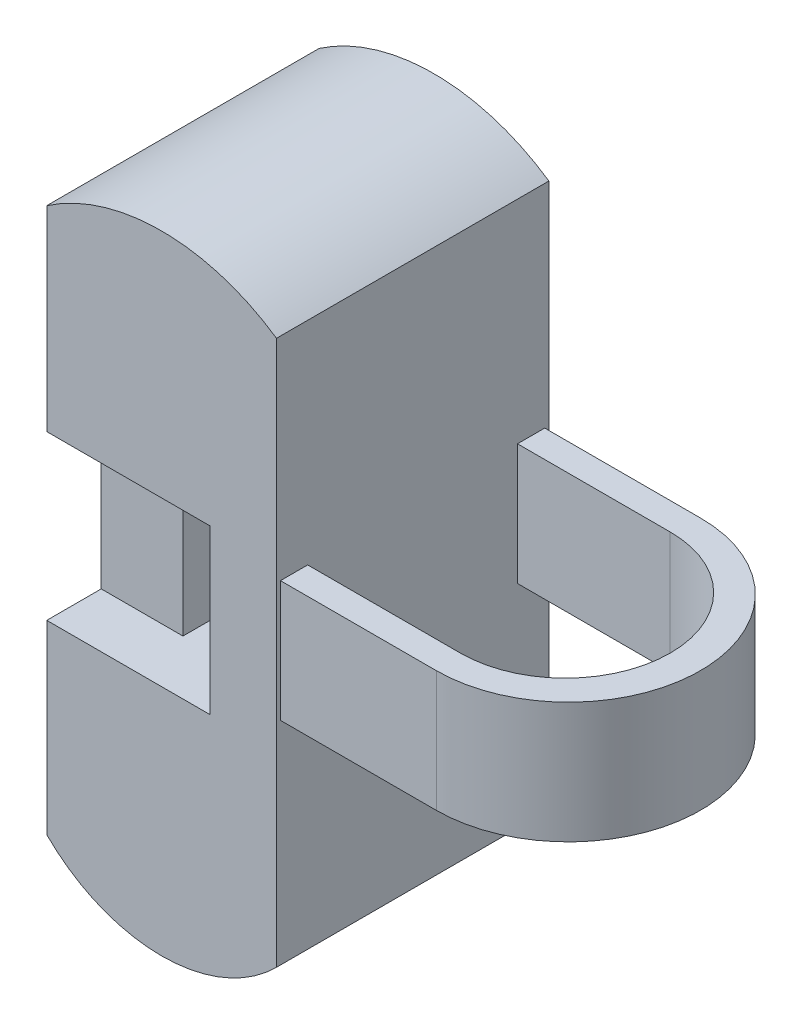
SolidWorks part; units mm, degrees
ref_plane "前基準面" through (0, 0, 0) normal (0, 0, 1) x (1, 0, 0)
ref_plane "上基準面" through (0, 0, 0) normal (0, 1, 0) x (1, 0, 0)
ref_plane "右基準面" through (0, 0, 0) normal (1, 0, 0) x (0, 0, -1)
sketch "草圖1" plane through (0, 0, 0) normal (0, 0, 1) x (1, 0, 0)
  line L0 (0, 0) -> (0, -20)
  line L1 (8.4342, 0) -> (8.4342, -20)
  arc A0 (0, 0) -> (8.4342, 0) centre (4.2171, -6.1607) cw
  arc A1 (8.4342, -20) -> (0, -20) centre (4.2171, -15.7829) cw
extrude "填料-伸長1" add sketch "草圖1" along normal mid plane 10 contours A0 L1 A1 L0
ref_plane "平面1" through (0, -10, 0) normal (0, 1, 0) x (1, 0, 0)
ref_plane "平面3" through (0, 0, 0) normal (0, 0, 1) x (1, 0, 0)
sketch "草圖13" plane through (0, 0, 0) normal (-1, 0, 0) x (0, 0, 1)
  point P0 (0, -10)
sketch "草圖19" plane through (-5.0319, -10, 0) normal (0, 1, 0) x (1, 0, 0)
  line L0 (8.3646, 4.8482) -> (19.187, 4.8482)
  line L1 (8.3646, -4.8546) -> (19.187, -4.8546)
  line L2 (8.3646, -4.8546) -> (8.3646, 4.8482)
  arc A0 (19.187, -4.8546) -> (19.187, 4.8482) centre (19.187, -0.0032) ccw
extrude "填料-伸長7" add sketch "草圖19" along normal mid plane 4.4417 contours A0 L0 L2 L1
sketch "草圖21" plane through (0, -7.7792, 0) normal (0, 1, 0) x (1, 0, 0)
  line L0 (11.2946, 4.8482) -> (11.2946, 3.8482)
  line L1 (8.4342, 4.8482) -> (14.1551, 4.8482) construction
  line L2 (8.4342, 3.8482) -> (14.0415, 3.8482)
  line L3 (8.4342, 4.8482) -> (8.4342, -4.8546) construction
  line L4 (11.6059, -4.8546) -> (11.6059, -3.8546)
  line L5 (8.4342, -4.8546) -> (14.1551, -4.8546) construction
  line L6 (8.4342, -3.8546) -> (14.0415, -3.8546)
  line L7 (8.4342, 3.8482) -> (8.4342, -3.8546)
  arc A0 (14.0415, 3.8482) -> (14.0415, -3.8546) centre (14.0415, -0.0032) cw
extrude "除料-伸長5" cut sketch "草圖21" against normal blind 4.5 contours L6 A0 L2 L7
sketch "草圖22" plane through (0, 0, 5) normal (0, 0, 1) x (1, 0, 0)
  line L0 (3, -13.1854) -> (0, -13.1854)
  line L1 (3, -7.1854) -> (6, -7.1854)
  line L2 (3, -7.1854) -> (3, -13.1854)
  line L3 (3, -13.1854) -> (6, -13.1854)
  line L4 (6, -7.1854) -> (6, -13.1854)
  line L5 (0, 0) -> (0, -20) construction
extrude "除料-伸長7" cut sketch "草圖22" against normal blind 10 contours L3 L4 L1 L2
sketch "草圖23" plane through (0, 0, 5) normal (0, 0, 1) x (1, 0, 0)
  line L0 (6, -7.1854) -> (6, -0.1854)
sketch "草圖24" plane through (0, 0, -5) normal (0, 0, -1) x (-1, 0, 0)
  line L0 (0, 0) -> (0, -20) construction
  line L1 (-3, -7.1854) -> (0, -7.1854)
  line L2 (-3, -7.1854) -> (-3, -13.1854)
  line L3 (-3, -13.1854) -> (0, -13.1854)
  line L4 (0, -7.1854) -> (0, -13.1854)
extrude "除料-伸長8" cut sketch "草圖24" against normal blind 2 contours L1 L4 L3 L2
sketch "草圖25" plane through (0, 0, 5) normal (0, 0, 1) x (1, 0, 0)
  line L1 (3, -7.1854) -> (0, -7.1854)
  line L2 (3, -7.1854) -> (3, -13.1854)
  line L3 (3, -13.1854) -> (0, -13.1854)
  line L4 (0, -7.1854) -> (0, -13.1854)
extrude "除料-伸長9" cut sketch "草圖25" against normal blind 2 contours L3 L4 L1 L2
